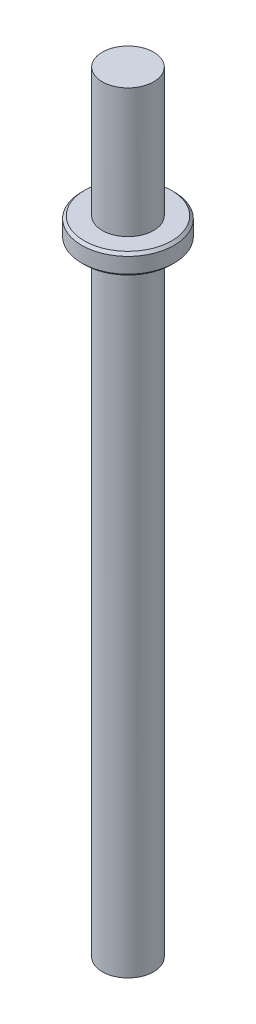
SolidWorks part; units mm, degrees
material "AISI 1020"
ref_plane "Front Plane" through (0, 0, 0) normal (0, 0, 1) x (1, 0, 0)
ref_plane "Top Plane" through (0, 0, 0) normal (0, 1, 0) x (1, 0, 0)
ref_plane "Right Plane" through (0, 0, 0) normal (1, 0, 0) x (0, 0, -1)
sketch "Sketch1" plane through (0, 0, 0) normal (0, 0, 1) x (1, 0, 0)
  line L1 (-12.9167, 138.125) -> (-2.9167, 138.125)
  line L2 (-12.9167, 138.125) -> (-12.9167, -161.875)
  line L3 (-12.9167, -161.875) -> (-2.9167, -161.875)
  line L4 (-2.9167, 138.125) -> (-2.9167, -161.875)
  line L5 (-12.9167, 138.125) -> (-2.9167, -161.875) construction
  line L6 (-12.9167, -161.875) -> (-2.9167, 138.125) construction
  point P0 (-7.9167, -11.875)
  dimension "D1" = 10
  dimension "D2" = 300
revolve "Revolve1" add sketch "Sketch1" angle 360 about L4
ref_plane "Plane1" through (0, 80, 0) normal (0, 1, 0) x (1, 0, 0)
sketch "Sketch4" plane through (0, 80, 0) normal (0, 1, 0) x (1, 0, 0)
  circle A0 centre (-2.9167, 0) radius 10 construction
  circle A1 centre (-2.9167, 0) radius 10
  circle A2 centre (-2.9167, 0) radius 18
  dimension "D1" = 8
extrude "Boss-Extrude3" add sketch "Sketch4" along normal blind 8
chamfer "Chamfer1" distance 1 angle 45 2 edges at (-2.9167, 80, 18) (-2.9167, 88, 18)
